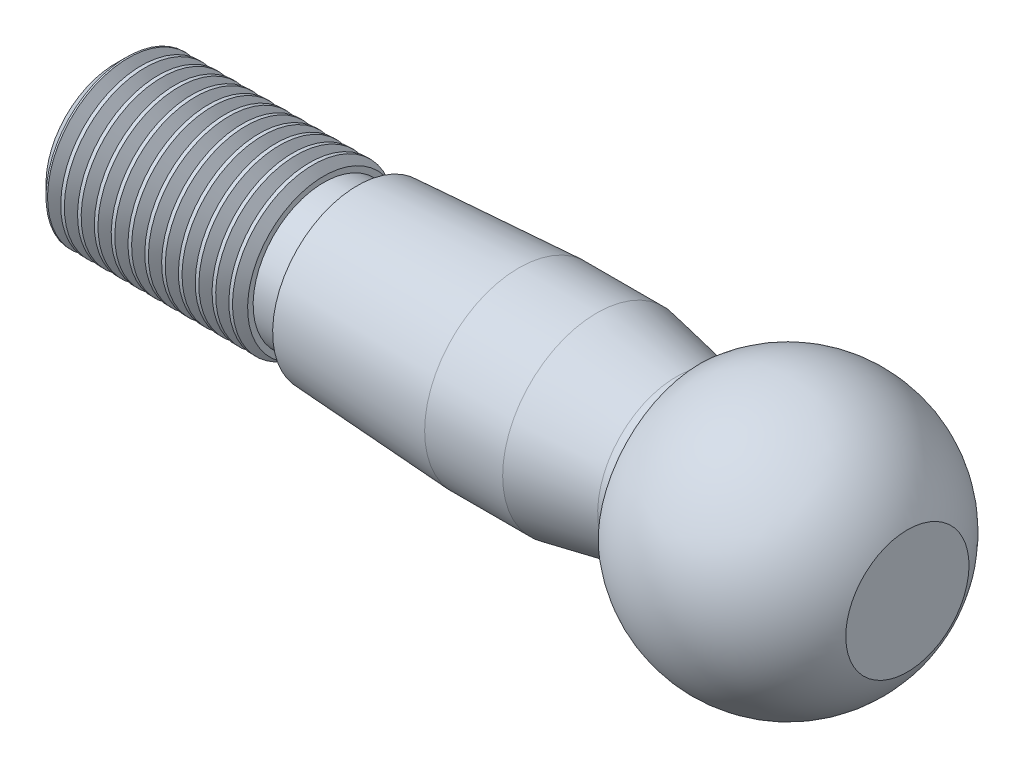
SolidWorks part; units mm, degrees
material "1.0718 (11SMnPb30)"
ref_plane "Ön Düzlem" through (0, 0, 0) normal (0, 0, 1) x (1, 0, 0)
ref_plane "Üst Düzlem" through (0, 0, 0) normal (0, 1, 0) x (1, 0, 0)
ref_plane "Sağ Düzlem" through (0, 0, 0) normal (1, 0, 0) x (0, 0, -1)
sketch "Çizim1" plane through (0, 0, 0) normal (0, 0, 1) x (1, 0, 0)
  line L0 (58.8899, -5.1515) -> (58.8899, -0.5721)
  line L1 (43.5, 2.4479) -> (43.5, 2.1714)
  line L2 (41.7138, 0.699) -> (35.8, 1.8485)
  line L3 (35.8, 1.8485) -> (30, 1.8485)
  line L4 (30, 1.8485) -> (18, 1.1485)
  line L5 (18, 1.1485) -> (17.4515, 0.1985)
  line L6 (17.2783, 0.0985) -> (15.5, 0.0985)
  line L7 (15.5, 0.0985) -> (15.5, 0.5089)
  line L8 (15.5, 0.5089) -> (15.2053, -0.0015)
  line L9 (15.2053, -0.0015) -> (14.7146, 0.8485)
  line L10 (14.7146, 0.8485) -> (14.4461, 0.8485)
  line L11 (14.4461, 0.8485) -> (13.9553, -0.0015)
  line L12 (13.9553, -0.0015) -> (13.4646, 0.8485)
  line L13 (13.4646, 0.8485) -> (13.1961, 0.8485)
  line L14 (13.1961, 0.8485) -> (12.7053, -0.0015)
  line L15 (12.7053, -0.0015) -> (12.2146, 0.8485)
  line L16 (12.2146, 0.8485) -> (11.9461, 0.8485)
  line L17 (11.9461, 0.8485) -> (11.4553, -0.0015)
  line L18 (11.4553, -0.0015) -> (10.9646, 0.8485)
  line L19 (10.9646, 0.8485) -> (10.6961, 0.8485)
  line L20 (10.6961, 0.8485) -> (10.2053, -0.0015)
  line L21 (10.2053, -0.0015) -> (9.7146, 0.8485)
  line L22 (9.7146, 0.8485) -> (9.4461, 0.8485)
  line L23 (9.4461, 0.8485) -> (8.9553, -0.0015)
  line L24 (8.9553, -0.0015) -> (8.4646, 0.8485)
  line L25 (8.4646, 0.8485) -> (8.1961, 0.8485)
  line L26 (8.1961, 0.8485) -> (7.7053, -0.0015)
  line L27 (7.7053, -0.0015) -> (7.2146, 0.8485)
  line L28 (6.9461, 0.8485) -> (6.4553, -0.0015)
  line L29 (6.4553, -0.0015) -> (5.9646, 0.8485)
  line L30 (5.9646, 0.8485) -> (5.6961, 0.8485)
  line L31 (5.6961, 0.8485) -> (5.2053, -0.0015)
  line L32 (5.2053, -0.0015) -> (4.7146, 0.8485)
  line L33 (4.7146, 0.8485) -> (4.4461, 0.8485)
  line L34 (4.4461, 0.8485) -> (3.9553, -0.0015)
  line L35 (3.9553, -0.0015) -> (3.4646, 0.8485)
  line L36 (3.4646, 0.8485) -> (3.1961, 0.8485)
  line L37 (3.1961, 0.8485) -> (2.7053, -0.0015)
  line L38 (2.7053, -0.0015) -> (2.2146, 0.8485)
  line L39 (2.2146, 0.8485) -> (1.9461, 0.8485)
  line L40 (1.9461, 0.8485) -> (1.4553, -0.0015)
  line L41 (1.4553, -0.0015) -> (0.9646, 0.8485)
  line L42 (0.9646, 0.8485) -> (0.8485, 0.8485)
  line L43 (0.8485, 0.8485) -> (0, 0)
  line L44 (0, 0) -> (0, -5.1515)
  line L45 (0, -5.1515) -> (6, -5.1515)
  line L46 (7.6, -5.1515) -> (58.8899, -5.1515)
  line L47 (17.4515, 0.1985) -> (17.2783, 0.0985)
  line L48 (6.9461, 0.8485) -> (7.2146, 0.8485)
  line L49 (6, -5.1515) -> (7.6, -5.1515)
  line L50 (7.6, -5.1515) -> (7.451, -5.1189)
  line L51 (0, -5.1515) -> (6, -5.1515)
  arc A0 (58.8899, -0.5721) -> (43.5, 2.4479) centre (50, -5.1515) ccw
  arc A1 (41.7138, 0.699) -> (43.5, 2.1714) centre (42, 2.1714) ccw
  circle A2 centre (6, -5.1515) radius 1.6
revolve "Döndür2" add sketch "Çizim1" angle 360 about L45
